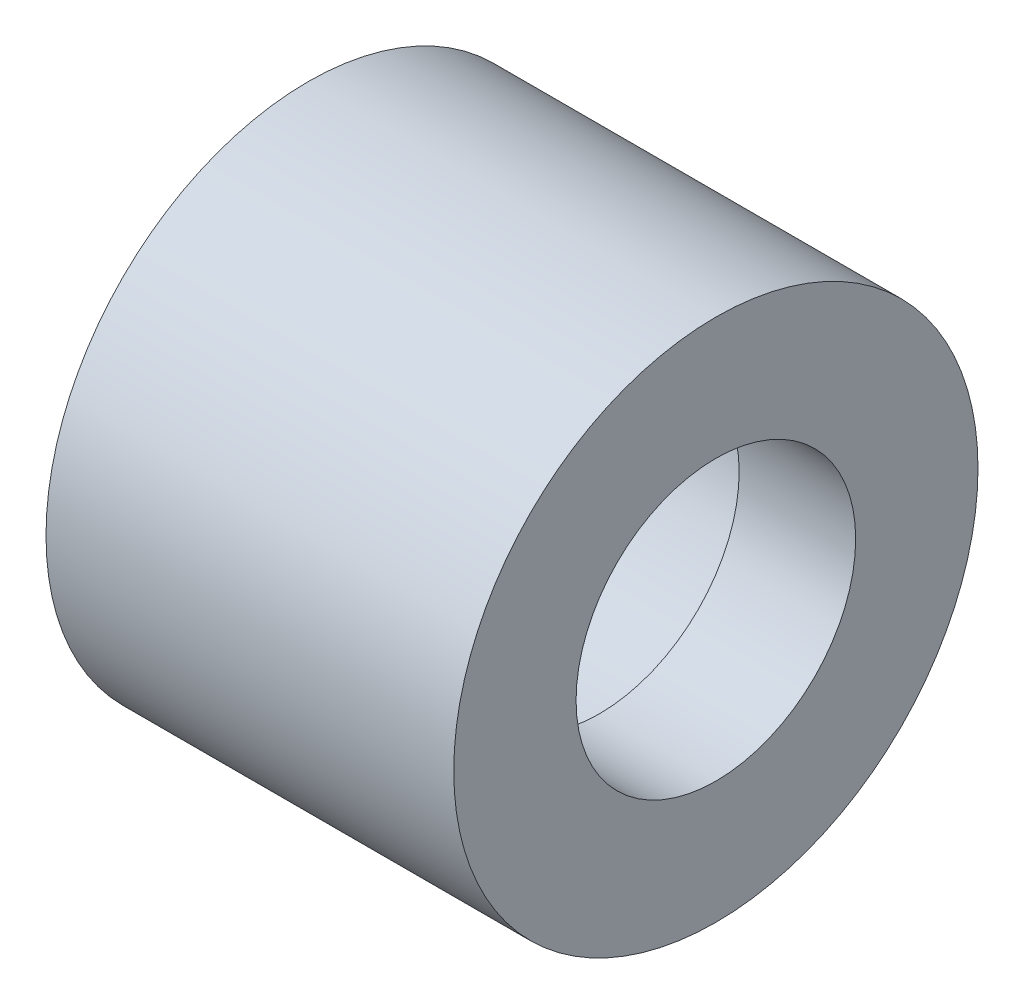
SolidWorks part; units mm, degrees
material "Copper"
ref_plane "Front Plane" through (0, 0, 0) normal (0, 0, 1) x (1, 0, 0)
ref_plane "Top Plane" through (0, 0, 0) normal (0, 1, 0) x (1, 0, 0)
ref_plane "Right Plane" through (0, 0, 0) normal (1, 0, 0) x (0, 0, -1)
sketch "Axial profile (mm)" plane through (0, 0, 0) normal (0, 0, 1) x (1, 0, 0)
  line L0 (-110, 0) -> (75, 0) construction
  line L1 (66, 3.175) -> (71, 3.175)
  line L2 (71, 3.175) -> (71, 2.4)
  line L3 (71, 2.4) -> (73, 2.4)
  line L4 (73, 2.4) -> (73, 4.5)
  line L5 (73, 4.5) -> (66, 4.5)
  line L6 (66, 4.5) -> (66, 3.175)
revolve "Full revolution" add sketch "Axial profile (mm)" angle 360 about L0
